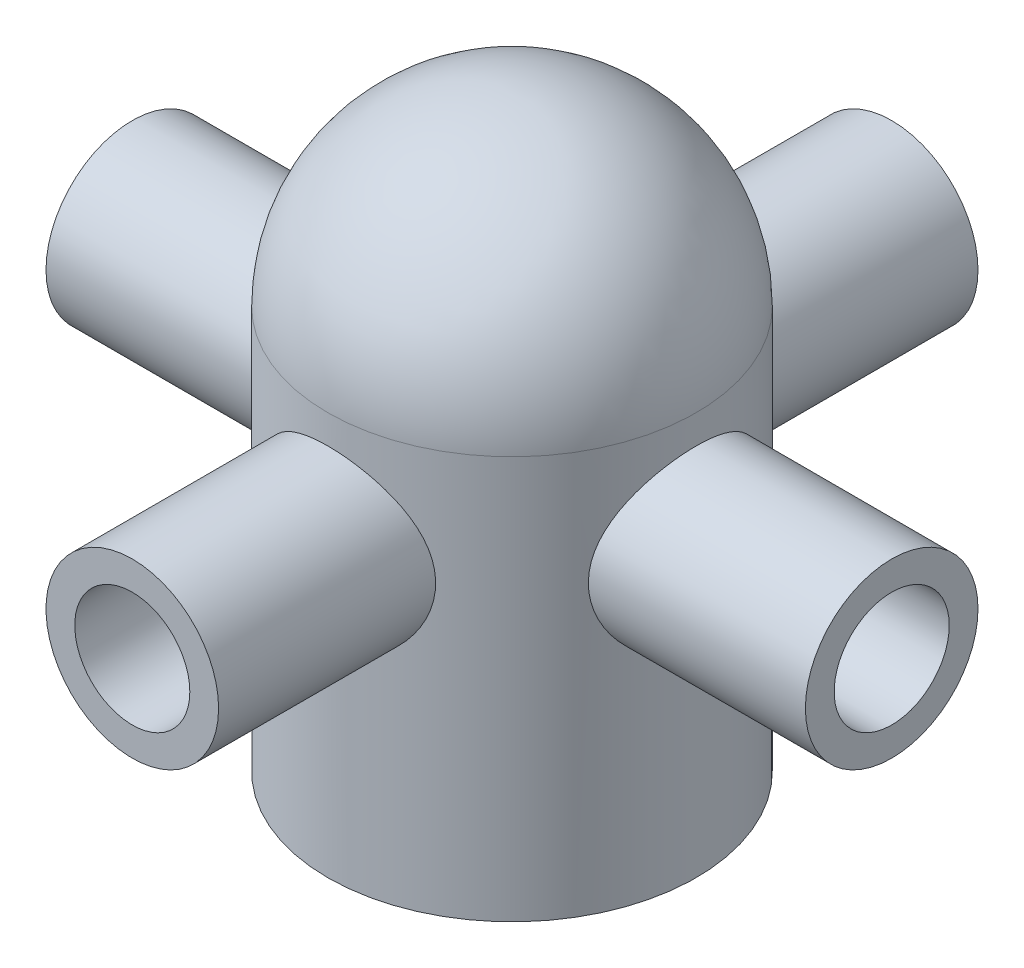
SolidWorks part; units mm, degrees
ref_plane "前视基准面" through (0, 0, 0) normal (0, 0, 1) x (1, 0, 0)
ref_plane "上视基准面" through (0, 0, 0) normal (0, 1, 0) x (1, 0, 0)
ref_plane "右视基准面" through (0, 0, 0) normal (1, 0, 0) x (0, 0, -1)
sketch "草图2" plane through (0, 0, 0) normal (0, 0, 1) x (1, 0, 0)
  line L0 (-16, 0) -> (-16, -35)
  line L1 (-16, -35) -> (-14, -35)
  line L2 (0, 0) -> (0, -33.1893) construction
  line L4 (-14, -35) -> (-14, 0)
  line L5 (-14, 0) -> (0, 0)
  line L6 (0, 16) -> (0, 0)
  arc A0 (0, 16) -> (-16, 0) centre (0, 0) ccw
  dimension "D1" = 32
  dimension "D2" = 35
  dimension "D3" = 14
revolve "旋转2" add sketch "草图2" angle 360 about L2
sketch "草图3" plane through (0, 0, 0) normal (0, 0, 1) x (1, 0, 0)
  circle A0 centre (0, -10) radius 7.5
  dimension "D1" = 15
  dimension "D2" = 10
extrude "凸台-拉伸2" add sketch "草图3" along normal blind 33
sketch "草图4" plane through (0, 0, 33) normal (0, 0, 1) x (1, 0, 0)
  circle A0 centre (0, -10) radius 5
  dimension "D1" = 10
extrude "切除-拉伸1" cut sketch "草图4" against normal blind 15
pattern_circular "阵列(圆周)2" count 4 over 360 about axis through (0, 0, 0) along (0, 1, 0) of "凸台-拉伸2", "切除-拉伸1"
